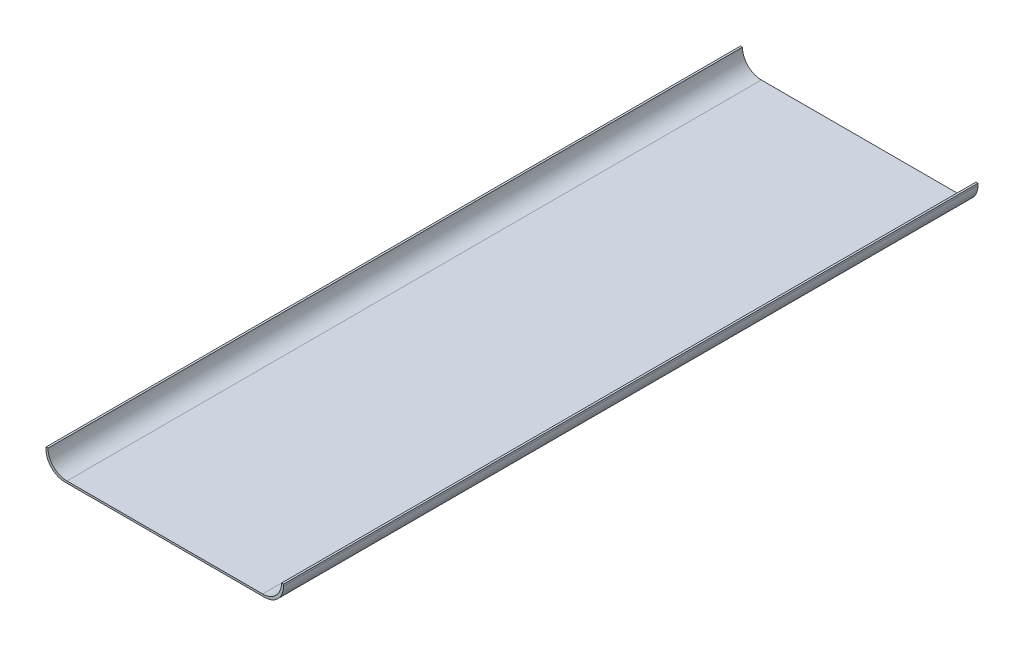
SolidWorks part; units mm, degrees
material "Thornel Mat VMA"
ref_plane "Front Plane" through (0, 0, 0) normal (0, 0, 1) x (1, 0, 0)
ref_plane "Top Plane" through (0, 0, 0) normal (0, 1, 0) x (1, 0, 0)
ref_plane "Right Plane" through (0, 0, 0) normal (1, 0, 0) x (0, 0, -1)
sketch "Sketch1" plane through (0, 0, 0) normal (0, 0, 1) x (1, 0, 0)
  line L0 (46.99, -39.37) -> (47.7838, -39.37)
  line L1 (-46.99, -39.37) -> (-47.7837, -39.37)
  line L3 (-39.37, -46.99) -> (39.37, -46.99)
  line L5 (44.7582, -44.7582) -> (46.99, -46.99) construction
  line L6 (-46.99, -46.99) -> (-44.7582, -44.7582) construction
  line L8 (-47.7837, -39.37) -> (-47.7837, -40.1637)
  line L9 (-40.1637, -47.7837) -> (40.1638, -47.7837)
  line L10 (47.7838, -39.37) -> (47.7838, -40.1637)
  line L11 (44.7582, -44.7582) -> (47.7838, -47.7837) construction
  line L12 (-47.7837, -47.7837) -> (-44.7582, -44.7582) construction
  arc A0 (-39.37, -46.99) -> (-46.99, -39.37) centre (-39.37, -39.37) cw
  arc A1 (46.99, -39.37) -> (39.37, -46.99) centre (39.37, -39.37) cw
  arc A2 (-40.1637, -47.7837) -> (-47.7837, -40.1637) centre (-40.1637, -40.1637) cw
  arc A3 (47.7838, -40.1637) -> (40.1638, -47.7837) centre (40.1638, -40.1637) cw
  point P0 (0, 0)
  point P12 (0, 0)
extrude "Boss-Extrude1" add sketch "Sketch1" along normal blind 279.4
